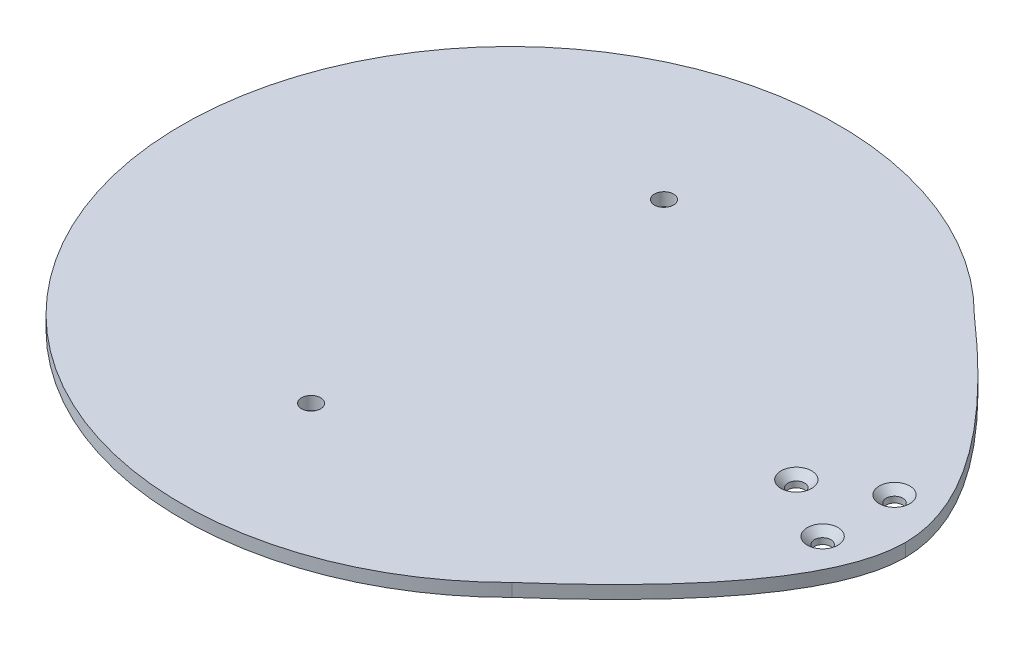
SolidWorks part; units mm, degrees
ref_plane "Ebene vorne" through (0, 0, 0) normal (0, 0, 1) x (1, 0, 0)
ref_plane "Ebene oben" through (0, 0, 0) normal (0, 1, 0) x (1, 0, 0)
ref_plane "Ebene rechts" through (0, 0, 0) normal (1, 0, 0) x (0, 0, -1)
sketch "Skizze1" plane through (0, 0, 0) normal (0, 1, 0) x (1, 0, 0)
  line L0 (28.9708, -44.5268) -> (28.9708, -44.5303)
  line L1 (60.1894, -0.0013) -> (47.1894, -0.0013) construction
  line L2 (47.1894, -0.0013) -> (-20.3106, -0.0013) construction
  arc A0 (28.9708, 44.5276) -> (28.9708, -44.5268) centre (-15.9502, 0.0004) ccw
  circle A1 centre (47.1894, -0.0013) radius 13
  spline S0 degree 2 poles (60.1894, -0.0013) (60.1894, 17.149) (28.9708, 44.5276) knots 0 0 0 1 1 1
  spline S1 degree 2 poles (60.1894, -0.0013) (60.1894, -17.1517) (28.9708, -44.5303) knots 0 0 0 1 1 1
  point P0 (0, 0)
  point P4 (0, 0)
  dimension "D1" = 13
  dimension "D2" = 67.5
extrude "Aufsatz-Linear austragen1" add sketch "Skizze1" along normal blind 2.5 contours S1 A1 S0 A0 L0 | A1
sketch "Skizze2" plane through (0, 2.5, 0) normal (0, 1, 0) x (1, 0, 0)
  line L0 (47.1894, -0.0013) -> (51.1894, 6.9269) construction
  line L1 (60.1894, -0.0013) -> (47.1894, -0.0013) construction
  circle A0 centre (47.1894, -0.0013) radius 3
  circle A1 centre (47.1894, -0.0013) radius 8
  circle A2 centre (51.1894, 6.9269) radius 1.6
  circle A3 centre (51.1894, -6.9296) radius 1.6
  circle A4 centre (39.1894, -0.0013) radius 1.6
  circle A5 centre (47.1894, -0.0013) radius 13
  point P13 (47.1894, -0.0013)
  dimension "D1" = 6
  dimension "D2" = 16
  dimension "D3" = 3.2
  dimension "D5" = 60
  dimension "D4" = 3
extrude "Schnitt-Linear austragen1" cut sketch "Skizze2" against normal through all contours A1 A2 | A2 L0 A1 | L0 A2 A1 | A1 A3 | A1 A3 | A1 A4 | A1 A4
chamfer "Fase1" distance 1.35 angle 45 3 edges at (51.1894, 2.5, 8.5296) (39.1894, 2.5, 1.6013) (51.1894, 2.5, -5.3269)
sketch "Skizze3" plane through (0, 2.5, 0) normal (0, 1, 0) x (1, 0, 0)
  line L0 (-20.3106, -34.0013) -> (-20.3106, 33.9987)
  circle A0 centre (-20.3106, 33.9987) radius 1.85
  circle A1 centre (-20.3106, -34.0013) radius 1.85
  point P4 (-20.3106, -0.0013)
  dimension "D2" = 3.7
  dimension "D3" = 3.7
  dimension "D1" = 68
extrude "Schnitt-Linear austragen2" cut sketch "Skizze3" against normal through all
